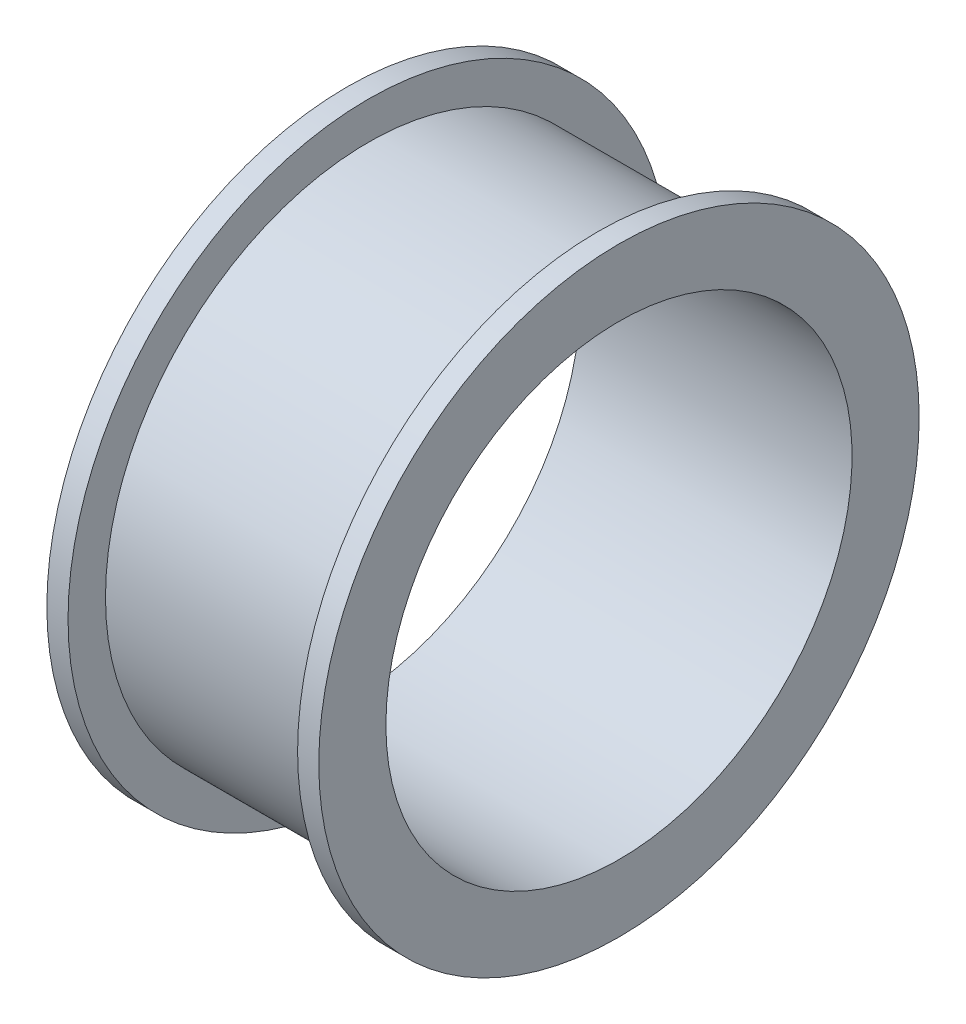
SolidWorks part; units mm, degrees
material "ABS"
ref_plane "Plano frontal" through (0, 0, 0) normal (0, 0, 1) x (1, 0, 0)
ref_plane "Plano superior" through (0, 0, 0) normal (0, 1, 0) x (1, 0, 0)
ref_plane "Plano direito" through (0, 0, 0) normal (1, 0, 0) x (0, 0, -1)
sketch "Esboço1" plane through (0, 0, 0) normal (1, 0, 0) x (0, 0, -1)
  circle A0 centre (0, 0) radius 6.6
  circle A1 centre (0, 0) radius 7.44
  dimension "D1" = 13.2
  dimension "D2" = 0.84
extrude "Ressalto-extrusão1" add sketch "Esboço1" along normal mid plane 6.5
sketch "Esboço2" plane through (3.25, 0, 0) normal (1, 0, 0) x (0, 0, -1)
  circle A0 centre (0, 0) radius 8.5
  dimension "D1" = 17
extrude "Ressalto-extrusão2" add sketch "Esboço2" along normal blind 0.6
mirror "Espelhar1" about plane through (0, 0, 0) normal (1, 0, 0) of "Ressalto-extrusão2"
sketch "Esboço3" plane through (3.85, 0, 0) normal (1, 0, 0) x (0, 0, -1)
  circle A0 centre (0, 0) radius 6.6
  dimension "D1" = 13.2
extrude "Corte-extrusão1" cut sketch "Esboço3" against normal through all
